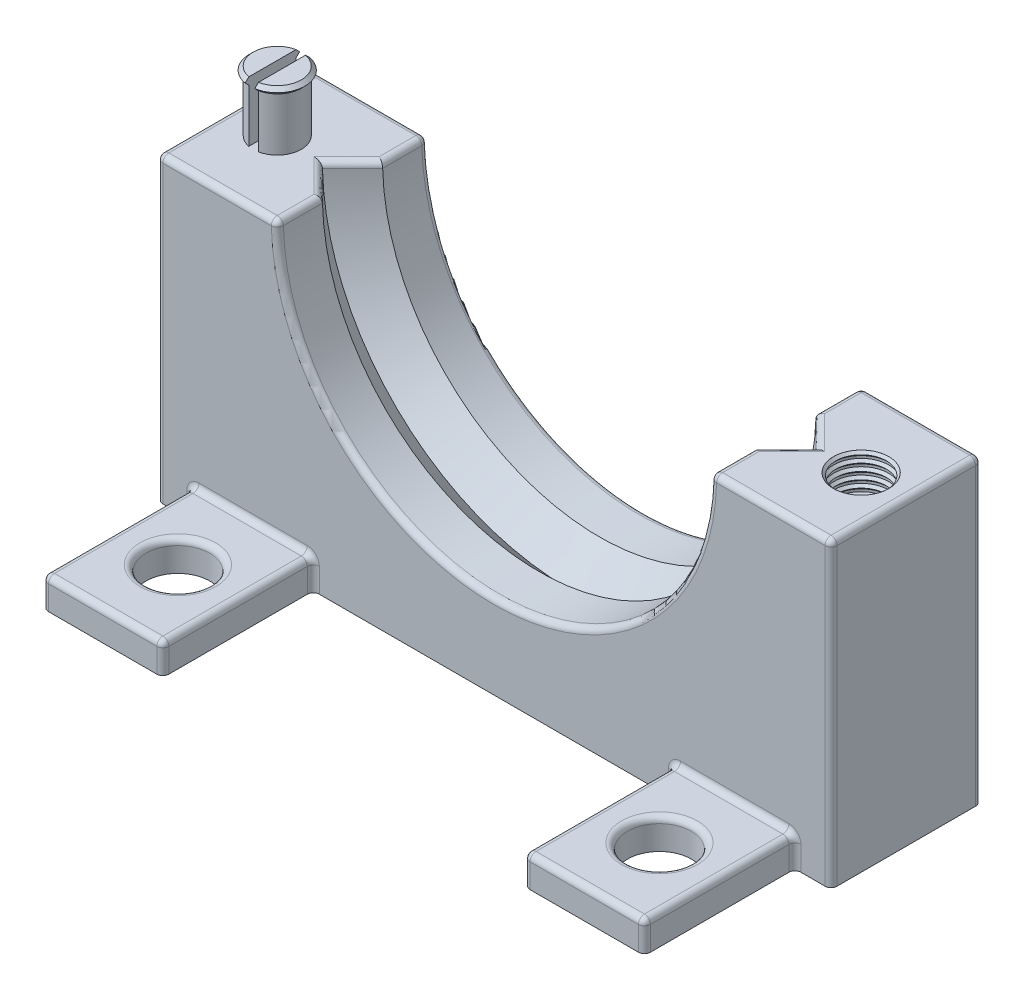
SolidWorks part; units mm, degrees
ref_plane "Front Plane" through (0, 0, 0) normal (0, 0, 1) x (1, 0, 0)
ref_plane "Top Plane" through (0, 0, 0) normal (0, 1, 0) x (1, 0, 0)
ref_plane "Right Plane" through (0, 0, 0) normal (1, 0, 0) x (0, 0, -1)
sketch "Sketch1" plane through (0, 0, 0) normal (0, 0, 1) x (1, 0, 0)
  line L0 (-35.56, 0) -> (35.56, 0)
  line L1 (35.56, 0) -> (35.56, 31.75)
  line L2 (35.56, 31.75) -> (22.86, 31.75)
  line L3 (-22.86, 31.75) -> (-35.56, 31.75)
  line L4 (-35.56, 31.75) -> (-35.56, 0)
  arc A0 (22.86, 31.75) -> (-22.86, 31.75) centre (0, 31.75) cw
  point P7 (0, 0)
  dimension "D2" = 22.86
  dimension "D1" = 31.75
  dimension "D3" = 12.7
extrude "Boss-Extrude1" add sketch "Sketch1" along normal blind 15.875
sketch "Sketch2" plane through (0, 31.75, 0) normal (0, 1, 0) x (1, 0, 0)
  line L0 (22.86, -11.1125) -> (26.035, -7.9375)
  line L2 (22.86, -15.875) -> (22.86, 0) construction
  line L3 (26.035, -7.9375) -> (22.86, -4.7625)
  line L4 (22.8654, -7.9375) -> (35.56, -7.9375) construction
  line L5 (22.86, -4.7625) -> (22.86, -11.1125)
  line L6 (35.56, -15.875) -> (35.56, 0) construction
  line L7 (0, 0) -> (0, -23.6383) construction
  dimension "D1" = 6.35
  dimension "D2" = 3.175
revolve "Cut-Revolve1" cut sketch "Sketch2" angle 360 about L7
sketch "Sketch6" plane through (0, 31.75, 0) normal (0, 1, 0) x (1, 0, 0)
  line L0 (26.035, -7.9375) -> (35.56, -7.9375) construction
  line L1 (35.56, -15.875) -> (35.56, 0) construction
  circle A0 centre (30.7975, -7.9375) radius 2.921
  dimension "D1" = 5.842
extrude "Cut-Extrude2" cut sketch "Sketch6" against normal blind 9.525
sketch "Sketch11" plane through (0, 31.75, 0) normal (0, 1, 0) x (1, 0, 0)
  line L0 (26.035, -7.9375) -> (35.56, -7.9375) construction
  line L1 (35.56, -15.875) -> (35.56, 0) construction
ref_plane "Plane1" through (0, 0, 7.9375) normal (0, 0, 1) x (1, 0, 0)
sketch "Sketch15" plane through (0, 0, 7.9375) normal (0, 0, 1) x (1, 0, 0)
  line L0 (-33.3375, 31.75) -> (-33.3375, 37.338)
  line L1 (-22.86, 31.75) -> (-35.56, 31.75) construction
  line L2 (-33.3375, 37.338) -> (-33.7185, 37.719)
  line L3 (-33.7185, 37.719) -> (-33.3375, 38.1)
  line L4 (-33.3375, 38.1) -> (-30.7975, 38.1)
  line L5 (-30.7975, 38.1) -> (-30.7975, 31.75)
  line L6 (-30.7975, 31.75) -> (-33.3375, 31.75)
  line L7 (-35.56, 31.75) -> (-35.56, 0) construction
  line L8 (-33.3375, 38.1) -> (-33.3375, 37.338) construction
  line L9 (-26.035, 31.75) -> (-35.56, 31.75) construction
  dimension "D1" = 2.54
  dimension "D3" = 6.35
  dimension "D4" = 90
  dimension "D5" = 2.921
revolve "Revolve2" add sketch "Sketch15" angle 360 about L5
sketch "Sketch12" plane through (0, 0, 7.9375) normal (0, 0, 1) x (1, 0, 0)
  line L0 (30.7975, 31.75) -> (30.7975, 26.6144) construction
  line L1 (26.035, 31.75) -> (35.56, 31.75) construction
  line L2 (27.8765, 30.48) -> (28.1305, 30.734)
  line L3 (27.8765, 31.242) -> (28.1305, 31.496)
  line L4 (28.1305, 31.496) -> (27.8765, 31.75)
  line L5 (27.8765, 31.75) -> (27.8765, 31.242)
  line L6 (30.7975, 31.75) -> (27.8765, 31.75) construction
  line L7 (28.1305, 30.734) -> (27.8765, 30.988)
  line L8 (27.8765, 30.988) -> (27.8765, 30.48)
  line L9 (27.8765, 29.718) -> (28.1305, 29.972)
  line L10 (28.1305, 29.972) -> (27.8765, 30.226)
  line L11 (27.8765, 30.226) -> (27.8765, 29.718)
  line L12 (27.8765, 28.956) -> (28.1305, 29.21)
  line L13 (28.1305, 29.21) -> (27.8765, 29.464)
  line L14 (27.8765, 29.464) -> (27.8765, 28.956)
  line L15 (27.8765, 28.194) -> (28.1305, 28.448)
  line L16 (28.1305, 28.448) -> (27.8765, 28.702)
  line L17 (27.8765, 28.702) -> (27.8765, 28.194)
  line L18 (27.8765, 27.432) -> (28.1305, 27.686)
  line L19 (28.1305, 27.686) -> (27.8765, 27.94)
  line L20 (27.8765, 27.94) -> (27.8765, 27.432)
  line L21 (27.8765, 26.67) -> (28.1305, 26.924)
  line L22 (28.1305, 26.924) -> (27.8765, 27.178)
  line L23 (27.8765, 27.178) -> (27.8765, 26.67)
  line L24 (27.8765, 25.908) -> (28.1305, 26.162)
  line L25 (28.1305, 26.162) -> (27.8765, 26.416)
  line L26 (27.8765, 26.416) -> (27.8765, 25.908)
  line L27 (27.8765, 25.146) -> (28.1305, 25.4)
  line L28 (28.1305, 25.4) -> (27.8765, 25.654)
  line L29 (27.8765, 25.654) -> (27.8765, 25.146)
  line L30 (27.8765, 24.384) -> (28.1305, 24.638)
  line L31 (28.1305, 24.638) -> (27.8765, 24.892)
  line L32 (27.8765, 24.892) -> (27.8765, 24.384)
  line L33 (27.8765, 23.622) -> (28.1305, 23.876)
  line L34 (28.1305, 23.876) -> (27.8765, 24.13)
  line L35 (27.8765, 24.13) -> (27.8765, 23.622)
  line L36 (27.8765, 22.86) -> (28.1305, 23.114)
  line L37 (28.1305, 23.114) -> (27.8765, 23.368)
  line L38 (27.8765, 23.368) -> (27.8765, 22.86)
  line L39 (27.8765, 22.098) -> (28.1305, 22.352)
  line L40 (28.1305, 22.352) -> (27.8765, 22.606)
  line L41 (27.8765, 22.606) -> (27.8765, 22.098)
  line L42 (27.8765, 21.336) -> (28.1305, 21.59)
  line L43 (28.1305, 21.59) -> (27.8765, 21.844)
  line L44 (27.8765, 21.844) -> (27.8765, 21.336)
  line L45 (27.8765, 20.574) -> (28.1305, 20.828)
  line L46 (28.1305, 20.828) -> (27.8765, 21.082)
  line L47 (27.8765, 21.082) -> (27.8765, 20.574)
  line L48 (27.8765, 19.812) -> (28.1305, 20.066)
  line L49 (28.1305, 20.066) -> (27.8765, 20.32)
  line L50 (27.8765, 20.32) -> (27.8765, 19.812)
  line L51 (27.8765, 19.05) -> (28.1305, 19.304)
  line L52 (28.1305, 19.304) -> (27.8765, 19.558)
  line L53 (27.8765, 19.558) -> (27.8765, 19.05)
  line L54 (27.8765, 18.288) -> (28.1305, 18.542)
  line L55 (28.1305, 18.542) -> (27.8765, 18.796)
  line L56 (27.8765, 18.796) -> (27.8765, 18.288)
  line L57 (27.8765, 17.526) -> (28.1305, 17.78)
  line L58 (28.1305, 17.78) -> (27.8765, 18.034)
  line L59 (27.8765, 18.034) -> (27.8765, 17.526)
  line L60 (27.8765, 16.764) -> (28.1305, 17.018)
  line L61 (28.1305, 17.018) -> (27.8765, 17.272)
  line L62 (27.8765, 17.272) -> (27.8765, 16.764)
  dimension "D1" = 2.921
  dimension "D2" = 0.508
  dimension "D3" = 90
  dimension "D4" = 20
revolve "Revolve1" add sketch "Sketch12" angle 360 about L0
sketch "Sketch16" plane through (0, 38.1, 0) normal (0, 1, 0) x (1, 0, 0)
  line L1 (-31.3055, -13.5293) -> (-30.2895, -13.5293)
  line L2 (-31.3055, -13.5293) -> (-31.3055, -2.3457)
  line L3 (-31.3055, -2.3457) -> (-30.2895, -2.3457)
  line L4 (-30.2895, -13.5293) -> (-30.2895, -2.3457)
  line L5 (-31.3055, -13.5293) -> (-30.2895, -2.3457) construction
  line L6 (-31.3055, -2.3457) -> (-30.2895, -13.5293) construction
  point P0 (-30.7975, -7.9375)
  dimension "D1" = 1.016
extrude "Cut-Extrude3" cut sketch "Sketch16" against normal up to surface (6.35 mm away) up to face at (-30.7975, 31.75, 10.4775)
sketch "Sketch17" plane through (0, 0, 0) normal (0, -1, 0) x (-1, 0, 0)
  line L1 (35.56, -15.875) -> (-35.56, -15.875) construction
  line L2 (31.75, -15.875) -> (19.05, -15.875)
  line L3 (31.75, -15.875) -> (31.75, -31.75)
  line L4 (31.75, -31.75) -> (19.05, -31.75)
  line L5 (19.05, -15.875) -> (19.05, -31.75)
  line L6 (0, 0) -> (0, -15.875) construction
  line L7 (-31.75, -15.875) -> (-19.05, -15.875)
  line L8 (-31.75, -15.875) -> (-31.75, -31.75)
  line L9 (-19.05, -15.875) -> (-19.05, -31.75)
  line L10 (-31.75, -31.75) -> (-19.05, -31.75)
  point P10 (25.4, -15.875)
  dimension "D1" = 12.7
  dimension "D2" = 15.875
  dimension "D3" = 25.4
extrude "Boss-Extrude2" add sketch "Sketch17" against normal blind 3.175
sketch "Sketch18" plane through (0, 3.175, 0) normal (0, 1, 0) x (1, 0, 0)
  line L0 (-25.4, -31.75) -> (-25.4, -15.875) construction
  line L1 (-19.05, -31.75) -> (-31.75, -31.75) construction
  line L2 (-31.75, -15.875) -> (-19.05, -15.875) construction
  line L3 (-25.4, -15.875) -> (-19.05, -23.8125) construction
  line L4 (-19.05, -15.875) -> (-19.05, -31.75) construction
  line L5 (-19.05, -23.8125) -> (-25.4, -23.8125) construction
  line L6 (0, 0) -> (0, -45.0309) construction
  circle A0 centre (-25.4, -23.8125) radius 3.3655
  circle A1 centre (25.4, -23.8125) radius 3.3655
  dimension "D1" = 6.731
extrude "Cut-Extrude4" cut sketch "Sketch18" against normal blind 3.175
fillet "Fillet1" radius 0.635 38 edges at (19.05, 1.5875, 15.875) (31.75, 1.5875, 15.875) (25.4, 3.175, 31.75) (19.05, 3.175, 23.8125) (25.4, 3.175, 15.875) (31.75, 3.175, 23.8125) (-25.4, 3.175, 27.178) (-31.75, 1.5875, 31.75) (-19.05, 1.5875, 31.75) (19.05, 1.5875, 31.75) (31.75, 1.5875, 31.75) (0, 8.89, 15.875) (0, 8.89, 0) (35.56, 15.875, 0) (35.56, 15.875, 15.875) (-35.56, 15.875, 15.875) (-35.56, 15.875, 0) (-25.4, 3.175, 15.875) (-19.05, 3.175, 23.8125) (-25.4, 3.175, 31.75) (-31.75, 3.175, 23.8125) (-24.4475, 31.75, 9.525) (-24.4475, 31.75, 6.35) (24.4475, 31.75, 9.525) (24.4475, 31.75, 6.35) (22.86, 31.75, 13.4937) (22.86, 31.75, 2.3812) (29.21, 31.75, 0) (35.56, 31.75, 7.9375) (29.21, 31.75, 15.875) (-22.86, 31.75, 13.4937) (-22.86, 31.75, 2.3813) (-29.21, 31.75, 0) (-35.56, 31.75, 7.9375) (-29.21, 31.75, 15.875) (25.4, 3.175, 20.447)
